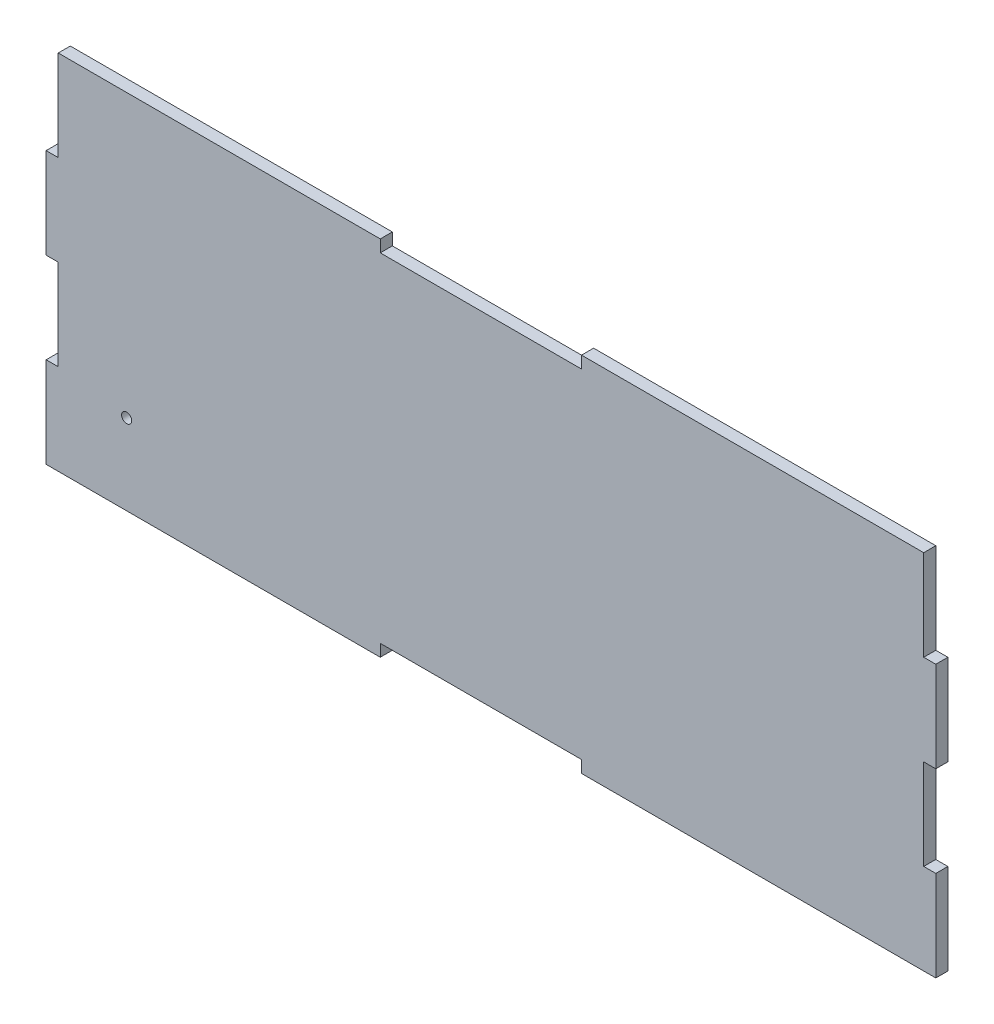
SolidWorks part; units mm, degrees
ref_plane "Front Plane" through (0, 0, 0) normal (0, 0, 1) x (1, 0, 0)
ref_plane "Top Plane" through (0, 0, 0) normal (0, 1, 0) x (1, 0, 0)
ref_plane "Right Plane" through (0, 0, 0) normal (1, 0, 0) x (0, 0, -1)
sketch "Sketch1" plane through (0, 0, 0) normal (0, 0, 1) x (1, 0, 0)
  line L8 (-2, 47) -> (78, 47)
  line L9 (78, 44) -> (128, 44)
  line L17 (213, -20.5) -> (213, 2)
  line L18 (-2, -43) -> (78, -43)
  line L23 (-2, -20.5) -> (-2, 2)
  line L37 (128, 47) -> (213, 47)
  line L44 (213, 24.5) -> (216, 24.5)
  line L50 (213, 2) -> (216, 2)
  line L58 (216, 24.5) -> (216, 2)
  line L63 (213, 24.5) -> (213, 47)
  line L64 (-2, 24.5) -> (-2, 47)
  line L65 (213, -43) -> (216, -43)
  line L67 (213, -20.5) -> (216, -20.5)
  line L68 (216, -43) -> (216, -20.5)
  line L69 (-2, -43) -> (-5, -43)
  line L71 (-2, -20.5) -> (-5, -20.5)
  line L72 (-5, -43) -> (-5, -20.5)
  line L73 (-2, 24.5) -> (-5, 24.5)
  line L75 (-2, 2) -> (-5, 2)
  line L76 (-5, 24.5) -> (-5, 2)
  line L77 (128, -43) -> (213, -43)
  line L79 (78, -43) -> (78, -40)
  line L80 (78, -40) -> (128, -40)
  line L81 (128, -43) -> (128, -40)
  line L84 (78, 47) -> (78, 44)
  line L86 (128, 47) -> (128, 44)
  circle A36 centre (15, -23) radius 1.25
  point P2 (0, 0)
  dimension "D7" = 2
  dimension "D9" = 2.5
  dimension "D10" = 20
  dimension "D28" = 22.5
  dimension "D31" = 3
  dimension "D49" = 3
  dimension "D11" = 20
  dimension "D6" = 2
  dimension "D17" = 90
  dimension "D20" = 22.5
  dimension "D29" = 22.5
  dimension "D30" = 22.5
  dimension "D32" = 3
  dimension "D33" = 3
  dimension "D34" = 3
  dimension "D47" = 22.5
  dimension "D48" = 3
  dimension "D50" = 22.5
  dimension "D51" = 50
  dimension "D53" = 80
  dimension "D54" = 3
  dimension "D56" = 50
  dimension "D57" = 80
  dimension "D88" = 22.5
extrude "Boss-Extrude1" add sketch "Sketch1" along normal blind 3
